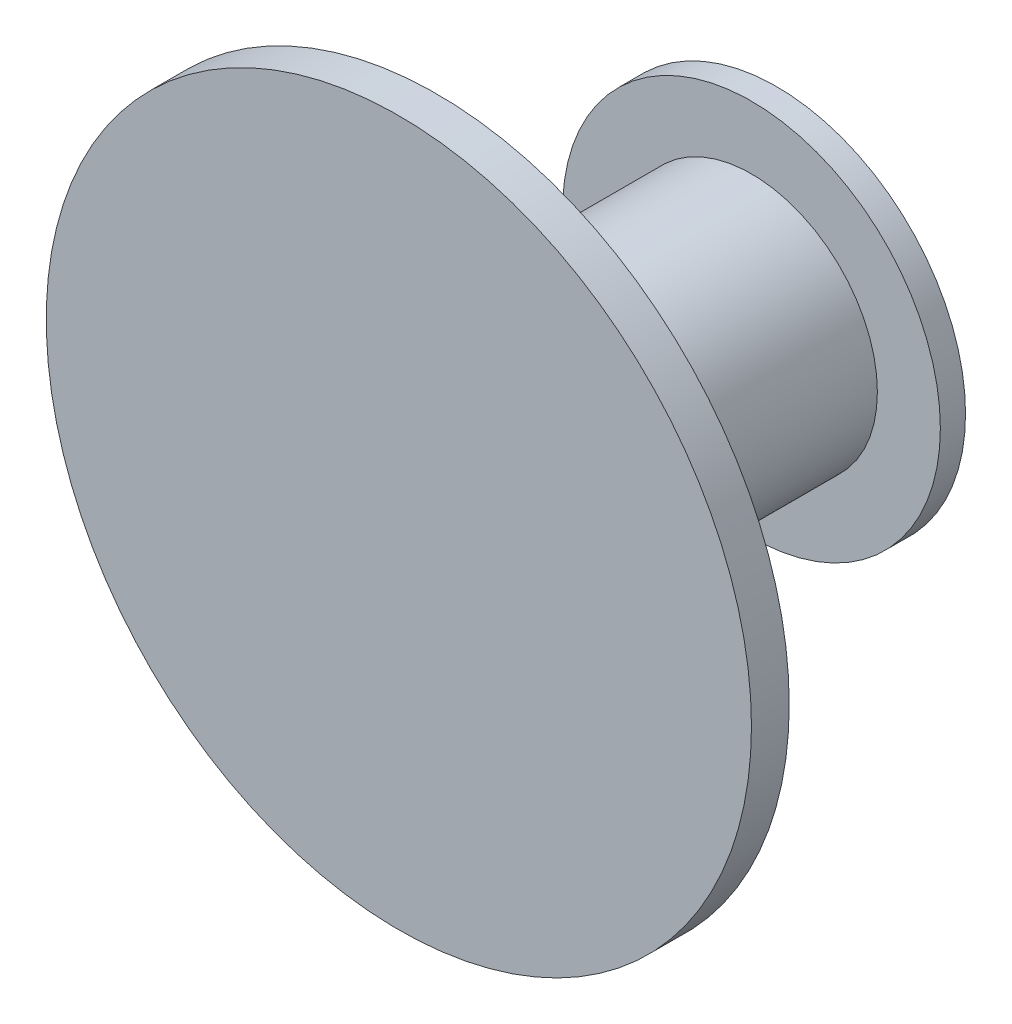
SolidWorks part; units mm, degrees
ref_plane "Front Plane" through (0, 0, 0) normal (0, 0, 1) x (1, 0, 0)
ref_plane "Top Plane" through (0, 0, 0) normal (0, 1, 0) x (1, 0, 0)
ref_plane "Right Plane" through (0, 0, 0) normal (1, 0, 0) x (0, 0, -1)
sketch "草图1" plane through (0, 0, 0) normal (0, 0, 1) x (1, 0, 0)
  circle A0 centre (0, 0) radius 150
  dimension "D1" = 300
extrude "凸台-拉伸1" add sketch "草图1" along normal blind 20
sketch "草图2" plane through (0, 0, 20) normal (0, 0, 1) x (1, 0, 0)
  circle A0 centre (0, 0) radius 100
  dimension "D1" = 200
extrude "凸台-拉伸2" add sketch "草图2" along normal blind 250
sketch "草图3" plane through (0, 0, 270) normal (0, 0, 1) x (1, 0, 0)
  circle A0 centre (0, 0) radius 280
  dimension "D1" = 560
extrude "凸台-拉伸3" add sketch "草图3" along normal blind 30
